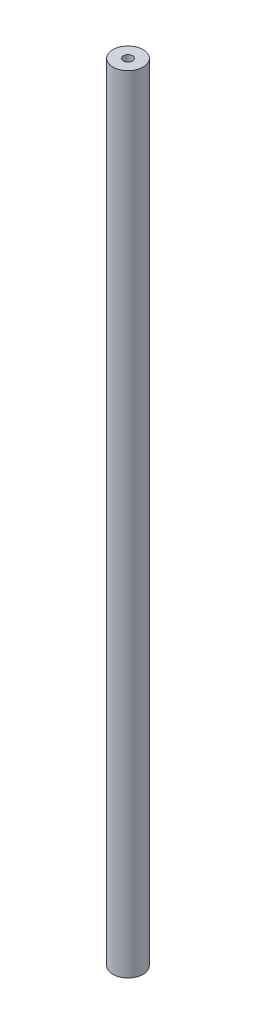
SolidWorks part; units mm, degrees
material "Alumina"
ref_plane "Front Plane" through (0, 0, 0) normal (0, 0, 1) x (1, 0, 0)
ref_plane "Top Plane" through (0, 0, 0) normal (0, 1, 0) x (1, 0, 0)
ref_plane "Right Plane" through (0, 0, 0) normal (1, 0, 0) x (0, 0, -1)
sketch "Sketch1" plane through (0, 0, 0) normal (0, 1, 0) x (1, 0, 0)
  circle A0 centre (0, 0) radius 0.75
  circle A1 centre (0, 0) radius 2.5
  dimension "D1" = 5
  dimension "D2" = 1.5
extrude "Boss-Extrude1" add sketch "Sketch1" along normal blind 130
